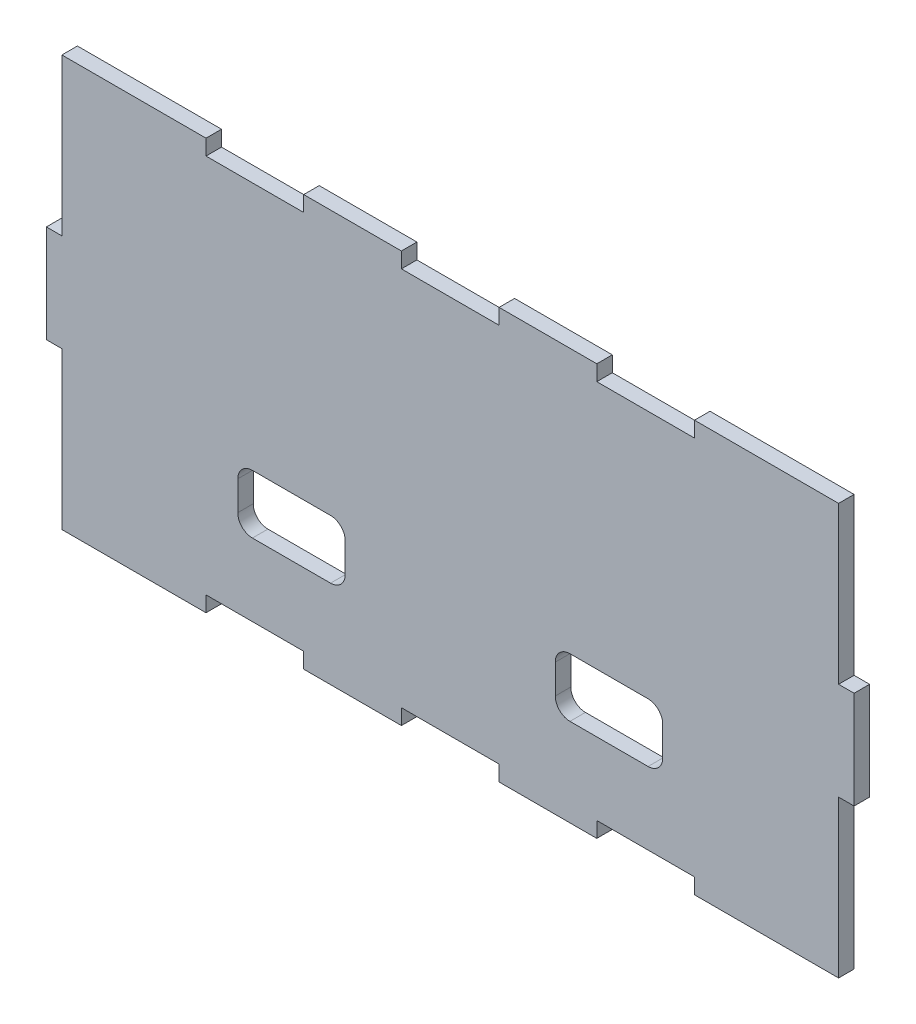
SolidWorks part; units mm, degrees
ref_plane "Plan de face" through (0, 0, 0) normal (0, 0, 1) x (1, 0, 0)
ref_plane "Plan de dessus" through (0, 0, 0) normal (0, 1, 0) x (1, 0, 0)
ref_plane "Plan de droite" through (0, 0, 0) normal (1, 0, 0) x (0, 0, -1)
sketch "Esquisse1" plane through (0, 0, 0) normal (0, 0, 1) x (1, 0, 0)
  line L0 (-82.675, 42.073) -> (-82.675, -42.073)
  line L1 (-82.675, 42.073) -> (82.675, 42.073)
  line L3 (-82.675, -42.073) -> (82.675, -42.073)
  line L4 (82.675, 42.073) -> (82.675, -42.073)
  point P4 (0, -42.073)
  point P6 (82.675, 0)
  point P7 (-82.675, 0)
  dimension "D1" = 84.146
  dimension "D2" = 165.35
extrude "Boss.-Extru.1" add sketch "Esquisse1" along normal blind 3.175
sketch "Esquisse4" plane through (0, 0, 3.175) normal (0, 0, 1) x (1, 0, 0)
  line L0 (-82.675, 42.073) -> (-82.675, -42.073) construction
  line L1 (-82.675, 10) -> (-76.325, 10)
  line L2 (-82.675, 10) -> (-82.675, -10)
  line L3 (-82.675, -10) -> (-76.325, -10)
  line L4 (-76.325, 10) -> (-76.325, -10)
  point P6 (-76.325, 0)
  dimension "D1" = 20
  dimension "D2" = 6.35
sketch "Esquisse2" plane through (0, 0, 3.175) normal (0, 0, 1) x (1, 0, 0)
  line L0 (-82.675, 42.073) -> (-82.675, -42.073) construction
  line L1 (-82.675, -42.073) -> (-79.5, -42.073)
  line L2 (-82.675, -42.073) -> (-82.675, -10)
  line L3 (-82.675, -10) -> (-79.5, -10)
  line L4 (-79.5, -42.073) -> (-79.5, -10)
  line L9 (-82.675, 10) -> (-79.5, 10)
  line L10 (-82.675, 10) -> (-82.675, 42.073)
  line L11 (-82.675, 42.073) -> (-79.5, 42.073)
  line L12 (-79.5, 10) -> (-79.5, 42.073)
  line L13 (-82.675, -42.073) -> (82.675, -42.073) construction
  line L14 (-82.675, 10) -> (-76.325, 10) construction
  line L15 (82.675, 42.073) -> (-82.675, 42.073) construction
  line L16 (-82.675, -10) -> (-76.325, -10) construction
  dimension "D1" = 3.175
extrude "Enlèv. mat.-Extru.1" cut sketch "Esquisse2" against normal through all
mirror "Symétrie1" about plane through (0, 0, 0) normal (1, 0, 0) of "Enlèv. mat.-Extru.1"
sketch "Esquisse3" plane through (0, 0, 3.175) normal (0, 0, 1) x (1, 0, 0)
  line L0 (-79.5, -42.073) -> (79.5, -42.073) construction
  line L1 (-10, -42.073) -> (10, -42.073)
  line L2 (-10, -42.073) -> (-10, -38.898)
  line L3 (-10, -38.898) -> (10, -38.898)
  line L4 (10, -42.073) -> (10, -38.898)
  line L6 (30, -42.073) -> (50, -42.073)
  line L7 (30, -42.073) -> (30, -38.898)
  line L8 (30, -38.898) -> (50, -38.898)
  line L9 (50, -42.073) -> (50, -38.898)
  line L10 (-30, -42.073) -> (-50, -42.073)
  line L11 (-30, -42.073) -> (-30, -38.898)
  line L12 (-30, -38.898) -> (-50, -38.898)
  line L13 (-50, -42.073) -> (-50, -38.898)
  point P14 (0, -38.898)
  point P16 (30, -40.4855)
  point P17 (10, -40.4855)
  dimension "D1" = 20
  dimension "D2" = 20
  dimension "D3" = 20
  dimension "D4" = 3.175
extrude "Enlèv. mat.-Extru.2" cut sketch "Esquisse3" against normal through all
mirror "Symétrie2" about plane through (0, 0, 0) normal (0, 1, 0) of "Enlèv. mat.-Extru.2"
sketch "Esquisse5" plane through (0, 0, 3.175) normal (0, 0, 1) x (1, 0, 0)
  line L0 (50, -42.073) -> (79.5, -42.073) construction
  line L1 (21.5, -12.073) -> (43.5, -12.073)
  line L2 (21.5, -12.073) -> (21.5, -24.073)
  line L3 (21.5, -24.073) -> (43.5, -24.073)
  line L4 (43.5, -12.073) -> (43.5, -24.073)
  line L5 (79.5, -42.073) -> (79.5, -10) construction
  point P8 (79.5, -26.0365)
  dimension "D1" = 22
  dimension "D2" = 18
  dimension "D3" = 36
  dimension "D4" = 12
extrude "Enlèv. mat.-Extru.3" cut sketch "Esquisse5" against normal through all
fillet "Congé1" radius 3 4 edges at (43.5, -24.073, 1.5875) (43.5, -12.073, 1.5875) (21.5, -24.073, 1.5875) (21.5, -12.073, 1.5875)
mirror "Symétrie3" about plane through (0, 0, 0) normal (1, 0, 0) of "Congé1", "Enlèv. mat.-Extru.3"
